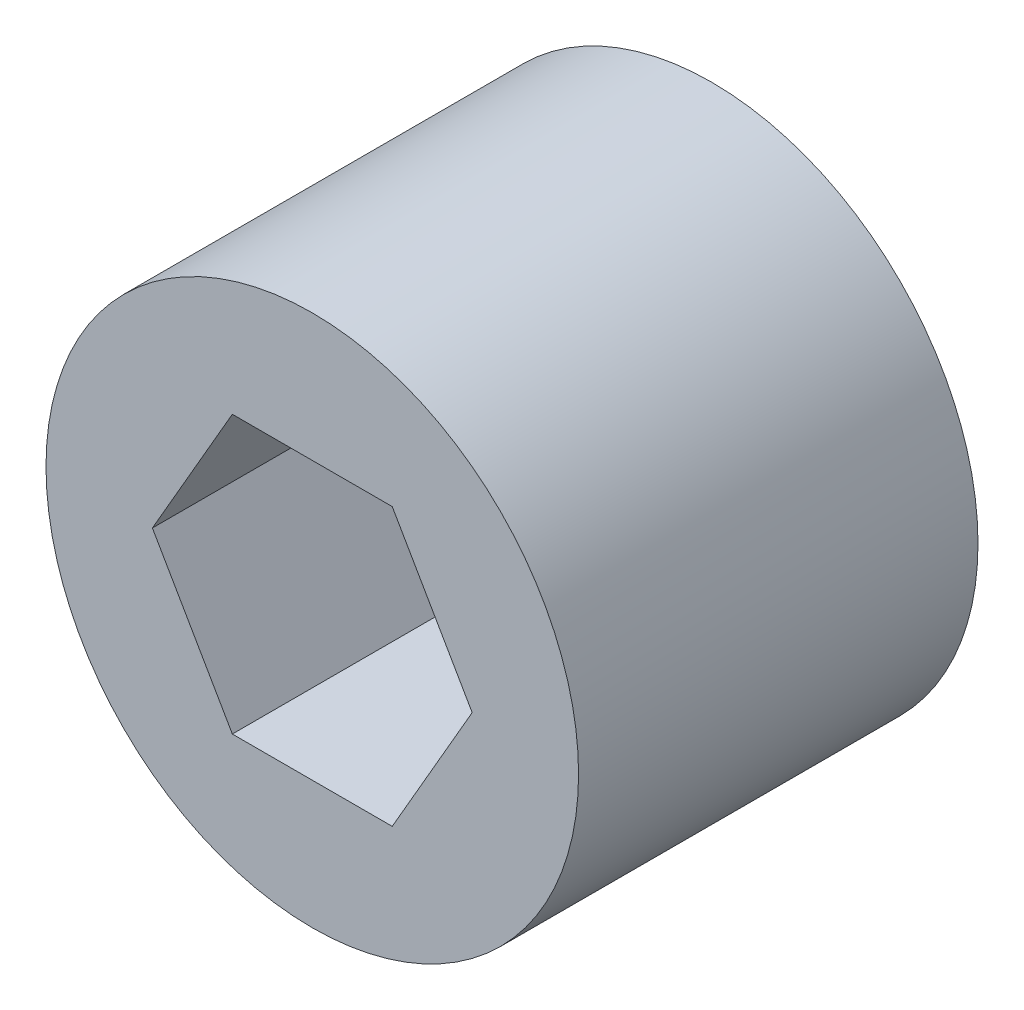
SolidWorks part; units mm, degrees
ref_plane "Front Plane" through (0, 0, 0) normal (0, 0, 1) x (1, 0, 0)
ref_plane "Top Plane" through (0, 0, 0) normal (0, 1, 0) x (1, 0, 0)
ref_plane "Right Plane" through (0, 0, 0) normal (1, 0, 0) x (0, 0, -1)
sketch "Sketch1" plane through (0, 0, 0) normal (0, 0, 1) x (1, 0, 0)
  line L1 (3.8128, -6.604) -> (7.6256, 0)
  line L2 (7.6256, 0) -> (3.8128, 6.604)
  line L3 (3.8128, 6.604) -> (-3.8128, 6.604)
  line L4 (-3.8128, 6.604) -> (-7.6256, 0)
  line L5 (-7.6256, 0) -> (-3.8128, -6.604)
  line L6 (-3.8128, -6.604) -> (3.8128, -6.604)
  circle A0 centre (0, 0) radius 6.604 construction
  circle A1 centre (0, 0) radius 12.7
  dimension "D2" = 25.4
  dimension "D1" = 13.208
extrude "Boss-Extrude1" add sketch "Sketch1" along normal blind 19.05
